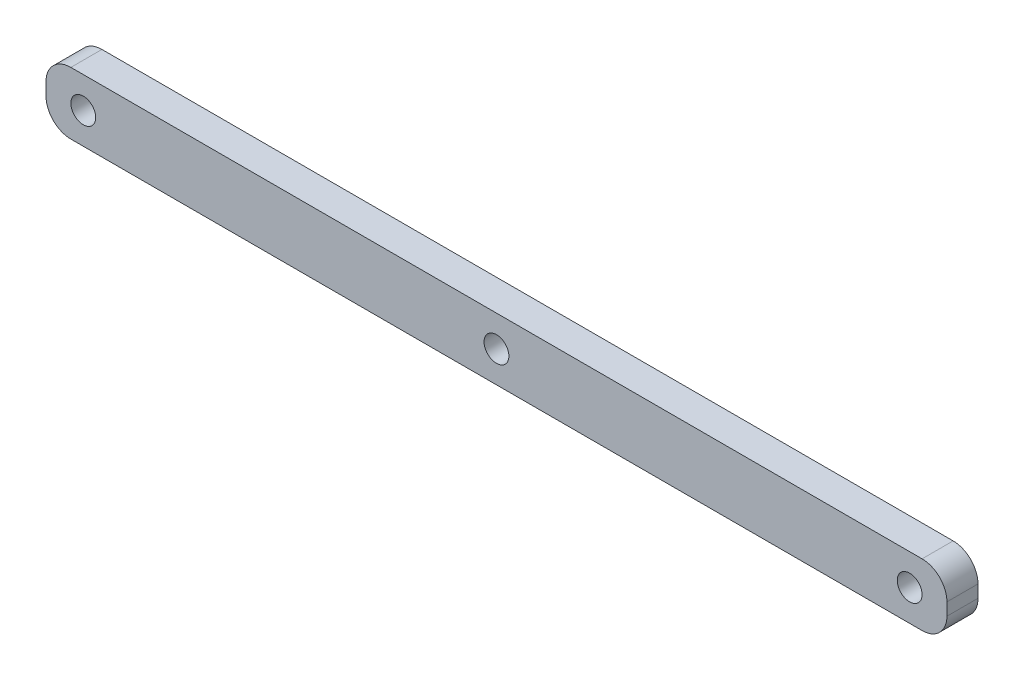
SolidWorks part; units mm, degrees
ref_plane "Płaszczyzna przednia" through (0, 0, 0) normal (0, 0, 1) x (1, 0, 0)
ref_plane "Płaszczyzna górna" through (0, 0, 0) normal (0, 1, 0) x (1, 0, 0)
ref_plane "Płaszczyzna prawa" through (0, 0, 0) normal (1, 0, 0) x (0, 0, -1)
sketch "Szkic1" plane through (0, 0, 0) normal (0, 0, 1) x (1, 0, 0)
  line L1 (-72.5, 5) -> (72.5, 5)
  line L2 (-72.5, 5) -> (-72.5, -5)
  line L3 (-72.5, -5) -> (72.5, -5)
  line L4 (72.5, 5) -> (72.5, -5)
  line L5 (-72.5, 5) -> (72.5, -5) construction
  line L6 (-72.5, -5) -> (72.5, 5) construction
  point P0 (0, 0)
  dimension "D1" = 10
  dimension "D2" = 145
extrude "Dodanie-wyciągnięcie1" add sketch "Szkic1" along normal blind 5
hole_wizard "Otwory ustalające Ø4.0mm1" positions "Szkic2" profile "Szkic3" hole size "Ø4.0" standard "Ansi Metric" end condition through all
sketch "Szkic2" plane through (0, 0, 5) normal (0, 0, 1) x (1, 0, 0)
  point P0 (0, 0)
  point P3 (-66.5, 0)
  point P5 (66.5, 0)
  dimension "D1" = 133
  dimension "D2" = 66.5
sketch "Szkic3" plane through (0, 0, 5) normal (1, 0, 0) x (0, -1, 0)
  line L0 (0, 0) -> (0, 5)
  line L1 (0, 5) -> (2, 5)
  line L2 (2, 5) -> (2, 0)
  line L5 (2, 0) -> (0, 0)
  line L11 (0, -6.35) -> (0, 107.95) construction
  dimension "Średnica otworu na wylot" = 4
  dimension "Głębokość otworu na wylot" = 5
fillet "Zaokrąglenie1" radius 4 4 edges at (-72.5, -5, 2.5) (-72.5, 5, 2.5) (72.5, 5, 2.5) (72.5, -5, 2.5)
equation "\"D2@Szkic2\"=\"D1@Szkic2\"/2"
